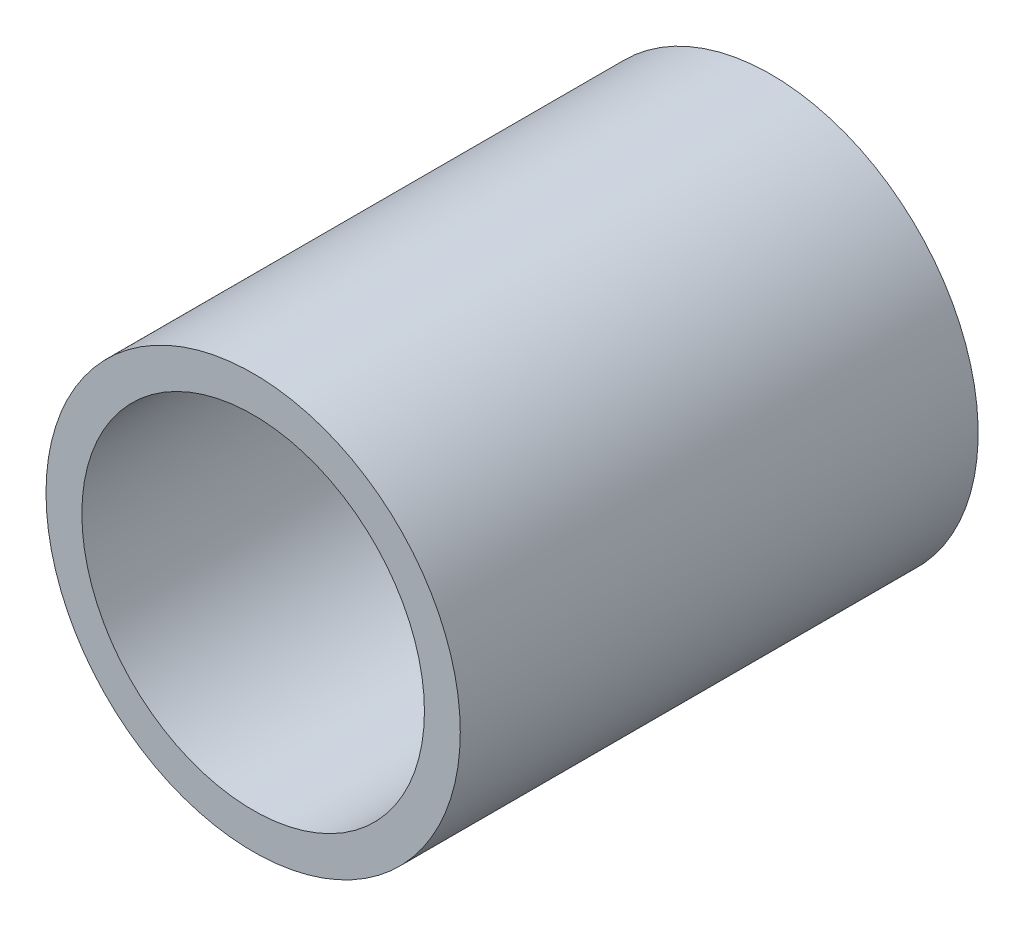
SolidWorks part; units mm, degrees
ref_plane "前视基准面" through (0, 0, 0) normal (0, 0, 1) x (1, 0, 0)
ref_plane "上视基准面" through (0, 0, 0) normal (0, 1, 0) x (1, 0, 0)
ref_plane "右视基准面" through (0, 0, 0) normal (1, 0, 0) x (0, 0, -1)
sketch "草图1" plane through (0, 0, 0) normal (0, 0, 1) x (1, 0, 0)
  circle A0 centre (0, 0) radius 2.6
extrude "凸台-拉伸1" add sketch "草图1" along normal blind 1.5
sketch "草图2" plane through (0, 0, 0) normal (0, 0, -1) x (-1, 0, 0)
  circle A0 centre (0, 0) radius 1.1
extrude "切除-拉伸1" cut sketch "草图2" against normal blind 0.6
sketch "草图3" plane through (0, 0, 0) normal (0, 0, -1) x (-1, 0, 0)
  circle A0 centre (0, 0) radius 2.6
  circle A1 centre (0, 0) radius 2.15
extrude "凸台-拉伸2" add sketch "草图3" along normal blind 1
sketch "草图4" plane through (0, 0, 1.5) normal (0, 0, 1) x (1, 0, 0)
  circle A0 centre (0, 0) radius 2.6
extrude "凸台-拉伸3" add sketch "草图4" along normal blind 4
sketch "草图5" plane through (0, 0, 5.5) normal (0, 0, 1) x (1, 0, 0)
  circle A0 centre (0, 0) radius 2.15
extrude "切除-拉伸2" cut sketch "草图5" against normal blind 4.1
